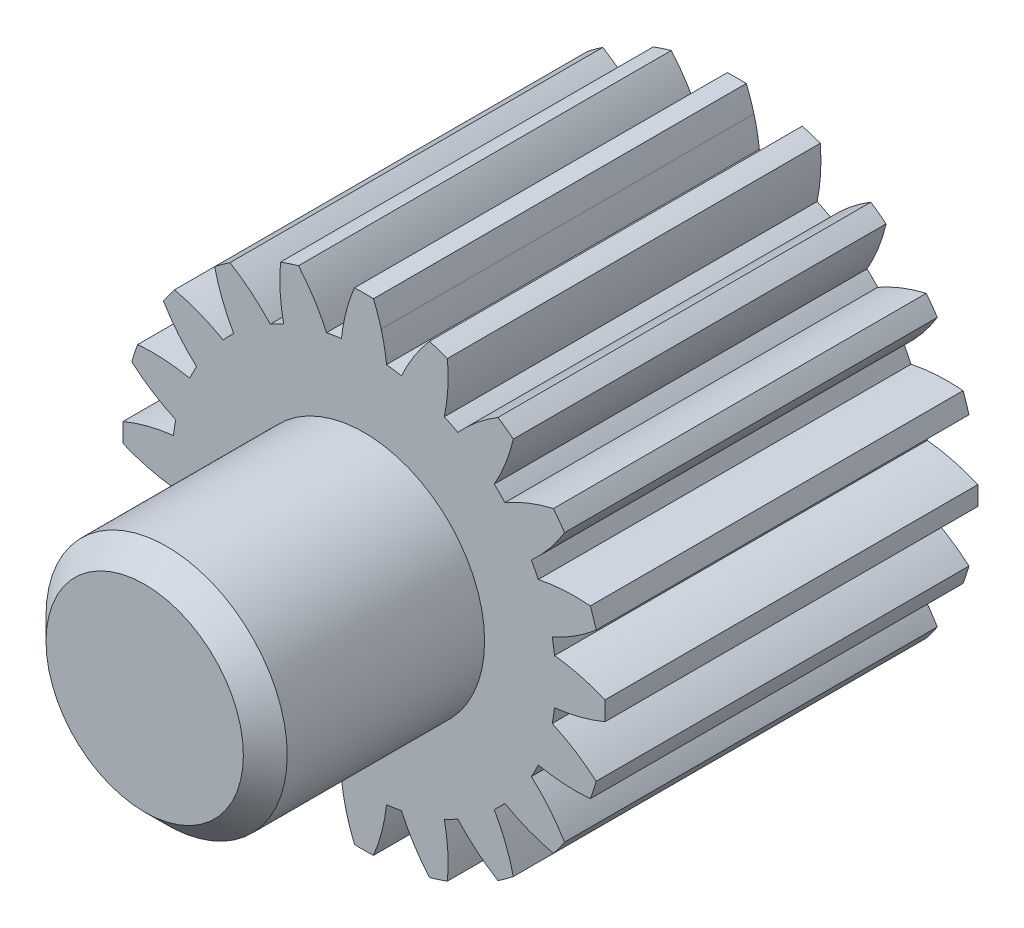
SolidWorks part; units mm, degrees
material "Сталь 45 ГОСТ 1050-88"
ref_plane "Front Plane" through (0, 0, 0) normal (0, 0, 1) x (1, 0, 0)
ref_plane "Top Plane" through (0, 0, 0) normal (0, 1, 0) x (1, 0, 0)
ref_plane "Right Plane" through (0, 0, 0) normal (1, 0, 0) x (0, 0, -1)
ref_plane "Ebene1" through (0, 0, 15) normal (0, 0, 1) x (1, 0, 0)
sketch "Skizze1" plane through (0, 0, 15) normal (0, 0, 1) x (1, 0, 0)
  arc A0 (-1.707, 8.5819) -> (-2.9858, 10.587) centre (-9.263, 5.1733) ccw
  arc A1 (-2.9858, 10.587) -> (-3.8073, 10.3201) centre (0, 0) ccw
  arc A2 (-3.8073, 10.3201) -> (-3.6633, 7.9463) centre (4.4532, 9.6299) ccw
  arc A3 (-3.6633, 7.9463) -> (-4.2754, 7.6343) centre (0, 0) ccw
  arc A4 (-4.2754, 7.6343) -> (-6.1113, 9.1462) centre (-10.4083, 2.0576) ccw
  arc A5 (-6.1113, 9.1462) -> (-6.81, 8.6385) centre (0, 0) ccw
  arc A6 (-6.81, 8.6385) -> (-5.9395, 6.4253) centre (1.2594, 10.5347) ccw
  arc A7 (-5.9395, 6.4253) -> (-6.4253, 5.9395) centre (0, 0) ccw
  arc A8 (-6.4253, 5.9395) -> (-8.6385, 6.81) centre (-10.5347, -1.2594) ccw
  arc A9 (-8.6385, 6.81) -> (-9.1462, 6.1113) centre (0, 0) ccw
  arc A10 (-9.1462, 6.1113) -> (-7.6343, 4.2754) centre (-2.0576, 10.4083) ccw
  arc A11 (-7.6343, 4.2754) -> (-7.9463, 3.6633) centre (0, 0) ccw
  arc A12 (-7.9463, 3.6633) -> (-10.3201, 3.8073) centre (-9.6299, -4.4532) ccw
  arc A13 (-10.3201, 3.8073) -> (-10.587, 2.9858) centre (0, 0) ccw
  arc A14 (-10.587, 2.9858) -> (-8.5819, 1.707) centre (-5.1733, 9.263) ccw
  arc A15 (-8.5819, 1.707) -> (-8.6893, 1.0285) centre (0, 0) ccw
  arc A16 (-8.6893, 1.0285) -> (-10.9915, 0.4319) centre (-7.7825, -7.211) ccw
  arc A17 (-10.9915, 0.4319) -> (-10.9915, -0.4319) centre (0, 0) ccw
  arc A18 (-10.9915, -0.4319) -> (-8.6893, -1.0285) centre (-7.7825, 7.211) ccw
  arc A19 (-8.6893, -1.0285) -> (-8.5819, -1.707) centre (0, 0) ccw
  arc A20 (-8.5819, -1.707) -> (-10.587, -2.9858) centre (-5.1733, -9.263) ccw
  arc A21 (-10.587, -2.9858) -> (-10.3201, -3.8073) centre (0, 0) ccw
  arc A22 (-10.3201, -3.8073) -> (-7.9463, -3.6633) centre (-9.6299, 4.4532) ccw
  arc A23 (-7.9463, -3.6633) -> (-7.6343, -4.2754) centre (0, 0) ccw
  arc A24 (-7.6343, -4.2754) -> (-9.1462, -6.1113) centre (-2.0576, -10.4083) ccw
  arc A25 (-9.1462, -6.1113) -> (-8.6385, -6.81) centre (0, 0) ccw
  arc A26 (-8.6385, -6.81) -> (-6.4253, -5.9395) centre (-10.5347, 1.2594) ccw
  arc A27 (-6.4253, -5.9395) -> (-5.9395, -6.4253) centre (0, 0) ccw
  arc A28 (-5.9395, -6.4253) -> (-6.81, -8.6385) centre (1.2594, -10.5347) ccw
  arc A29 (-6.81, -8.6385) -> (-6.1113, -9.1462) centre (0, 0) ccw
  arc A30 (-6.1113, -9.1462) -> (-4.2754, -7.6343) centre (-10.4083, -2.0576) ccw
  arc A31 (-4.2754, -7.6343) -> (-3.6633, -7.9463) centre (0, 0) ccw
  arc A32 (-3.6633, -7.9463) -> (-3.8073, -10.3201) centre (4.4532, -9.6299) ccw
  arc A33 (-3.8073, -10.3201) -> (-2.9858, -10.587) centre (0, 0) ccw
  arc A34 (-2.9858, -10.587) -> (-1.707, -8.5819) centre (-9.263, -5.1733) ccw
  arc A35 (-1.707, -8.5819) -> (-1.0285, -8.6893) centre (0, 0) ccw
  arc A36 (-1.0285, -8.6893) -> (-0.4319, -10.9915) centre (7.211, -7.7825) ccw
  arc A37 (-0.4319, -10.9915) -> (0.4319, -10.9915) centre (0, 0) ccw
  arc A38 (0.4319, -10.9915) -> (1.0285, -8.6893) centre (-7.211, -7.7825) ccw
  arc A39 (1.0285, -8.6893) -> (1.707, -8.5819) centre (0, 0) ccw
  arc A40 (1.707, -8.5819) -> (2.9858, -10.587) centre (9.263, -5.1733) ccw
  arc A41 (2.9858, -10.587) -> (3.8073, -10.3201) centre (0, 0) ccw
  arc A42 (3.8073, -10.3201) -> (3.6633, -7.9463) centre (-4.4532, -9.6299) ccw
  arc A43 (3.6633, -7.9463) -> (4.2754, -7.6343) centre (0, 0) ccw
  arc A44 (4.2754, -7.6343) -> (6.1113, -9.1462) centre (10.4083, -2.0576) ccw
  arc A45 (6.1113, -9.1462) -> (6.81, -8.6385) centre (0, 0) ccw
  arc A46 (6.81, -8.6385) -> (5.9395, -6.4253) centre (-1.2594, -10.5347) ccw
  arc A47 (5.9395, -6.4253) -> (6.4253, -5.9395) centre (0, 0) ccw
  arc A48 (6.4253, -5.9395) -> (8.6385, -6.81) centre (10.5347, 1.2594) ccw
  arc A49 (8.6385, -6.81) -> (9.1462, -6.1113) centre (0, 0) ccw
  arc A50 (9.1462, -6.1113) -> (7.6343, -4.2754) centre (2.0576, -10.4083) ccw
  arc A51 (7.6343, -4.2754) -> (7.9463, -3.6633) centre (0, 0) ccw
  arc A52 (7.9463, -3.6633) -> (10.3201, -3.8073) centre (9.6299, 4.4532) ccw
  arc A53 (10.3201, -3.8073) -> (10.587, -2.9858) centre (0, 0) ccw
  arc A54 (10.587, -2.9858) -> (8.5819, -1.707) centre (5.1733, -9.263) ccw
  arc A55 (8.5819, -1.707) -> (8.6893, -1.0285) centre (0, 0) ccw
  arc A56 (8.6893, -1.0285) -> (10.9915, -0.4319) centre (7.7825, 7.211) ccw
  arc A57 (10.9915, -0.4319) -> (10.9915, 0.4319) centre (0, 0) ccw
  arc A58 (10.9915, 0.4319) -> (8.6893, 1.0285) centre (7.7825, -7.211) ccw
  arc A59 (8.6893, 1.0285) -> (8.5819, 1.707) centre (0, 0) ccw
  arc A60 (8.5819, 1.707) -> (10.587, 2.9858) centre (5.1733, 9.263) ccw
  arc A61 (10.587, 2.9858) -> (10.3201, 3.8073) centre (0, 0) ccw
  arc A62 (10.3201, 3.8073) -> (7.9463, 3.6633) centre (9.6299, -4.4532) ccw
  arc A63 (7.9463, 3.6633) -> (7.6343, 4.2754) centre (0, 0) ccw
  arc A64 (7.6343, 4.2754) -> (9.1462, 6.1113) centre (2.0576, 10.4083) ccw
  arc A65 (9.1462, 6.1113) -> (8.6385, 6.81) centre (0, 0) ccw
  arc A66 (8.6385, 6.81) -> (6.4253, 5.9395) centre (10.5347, -1.2594) ccw
  arc A67 (6.4253, 5.9395) -> (5.9395, 6.4253) centre (0, 0) ccw
  arc A68 (5.9395, 6.4253) -> (6.81, 8.6385) centre (-1.2594, 10.5347) ccw
  arc A69 (6.81, 8.6385) -> (6.1113, 9.1462) centre (0, 0) ccw
  arc A70 (6.1113, 9.1462) -> (4.2754, 7.6343) centre (10.4083, 2.0576) ccw
  arc A71 (4.2754, 7.6343) -> (3.6633, 7.9463) centre (0, 0) ccw
  arc A72 (3.6633, 7.9463) -> (3.8073, 10.3201) centre (-4.4532, 9.6299) ccw
  arc A73 (3.8073, 10.3201) -> (2.9858, 10.587) centre (0, 0) ccw
  arc A74 (2.9858, 10.587) -> (1.707, 8.5819) centre (9.263, 5.1733) ccw
  arc A75 (1.707, 8.5819) -> (1.0285, 8.6893) centre (0, 0) ccw
  arc A76 (1.0285, 8.6893) -> (0.4319, 10.9915) centre (-7.211, 7.7825) ccw
  arc A77 (0.4319, 10.9915) -> (-0.4319, 10.9915) centre (0, 0) ccw
  arc A78 (-0.4319, 10.9915) -> (-1.0285, 8.6893) centre (7.211, 7.7825) ccw
  arc A79 (-1.0285, 8.6893) -> (-1.707, 8.5819) centre (0, 0) ccw
extrude "Aufsatz-Linear austragen1" add sketch "Skizze1" against normal blind 17
sketch "Skizze2" plane through (0, 0, 15) normal (0, 0, 1) x (1, 0, 0)
  circle A0 centre (0, 0) radius 5.5
  point P0 (0, 0)
extrude "Aufsatz-Linear austragen3" add sketch "Skizze2" along normal blind 10
sketch "Skizze4" plane through (0, 0, 15) normal (0, 0, 1) x (1, 0, 0)
  circle A0 centre (0, 0) radius 4
sketch "Skizze5" plane through (0, 0, 15) normal (0, 0, 1) x (1, 0, 0)
  circle A0 centre (0, 0) radius 10
split line "Trennlinie1"
chamfer "Fase1" distance 1 angle 45 1 edges at (5.5, 0, 25)
